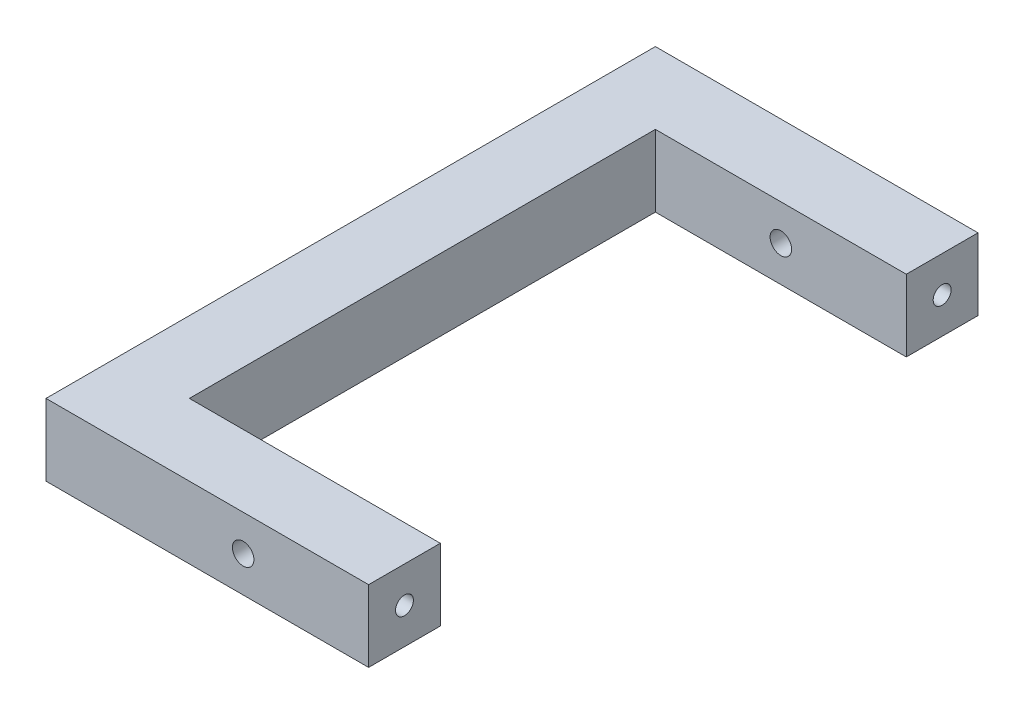
SolidWorks part; units mm, degrees
ref_plane "Front Plane" through (0, 0, 0) normal (0, 0, 1) x (1, 0, 0)
ref_plane "Top Plane" through (0, 0, 0) normal (0, 1, 0) x (1, 0, 0)
ref_plane "Right Plane" through (0, 0, 0) normal (1, 0, 0) x (0, 0, -1)
sketch "Sketch1" plane through (0, 0, 0) normal (0, 1, 0) x (1, 0, 0)
  line L0 (0, 170) -> (0, -194.0717) construction
  line L1 (-287.8827, 0) -> (277.329, 0) construction
  line L2 (0, 170) -> (180, 170)
  line L3 (180, 170) -> (180, 130)
  line L4 (180, 130) -> (40, 130)
  line L5 (40, 130) -> (40, -130)
  line L6 (0, 170) -> (0, -170)
  line L7 (180, -130) -> (40, -130)
  line L8 (180, -170) -> (180, -130)
  line L9 (0, -170) -> (180, -170)
  point P12 (0, 0)
  point P13 (40, 0)
  dimension "D1" = 170
  dimension "D2" = 180
  dimension "D3" = 40
  dimension "D4" = 40
extrude "Boss-Extrude1" add sketch "Sketch1" along normal blind 40
sketch "Sketch2" plane through (0, 0, 170) normal (0, 0, 1) x (1, 0, 0)
  line L0 (180, 40) -> (180, 0) construction
  line L1 (0, 0) -> (180, 0) construction
  circle A0 centre (110, 20) radius 6
  dimension "D1" = 12
  dimension "D2" = 70
  dimension "D3" = 20
extrude "Cut-Extrude1" cut sketch "Sketch2" against normal blind 395
sketch "Sketch3" plane through (180, 0, 0) normal (1, 0, 0) x (0, 0, -1)
  line L0 (-130, 40) -> (-130, 0) construction
  line L1 (-170, 0) -> (-130, 0) construction
  line L2 (0, 22) -> (0, -22) construction
  circle A0 centre (-150, 20) radius 5
  circle A1 centre (150, 20) radius 5
  dimension "D3" = 10
  dimension "D1" = 20
  dimension "D2" = 20
extrude "Cut-Extrude2" cut sketch "Sketch3" against normal blind 50
